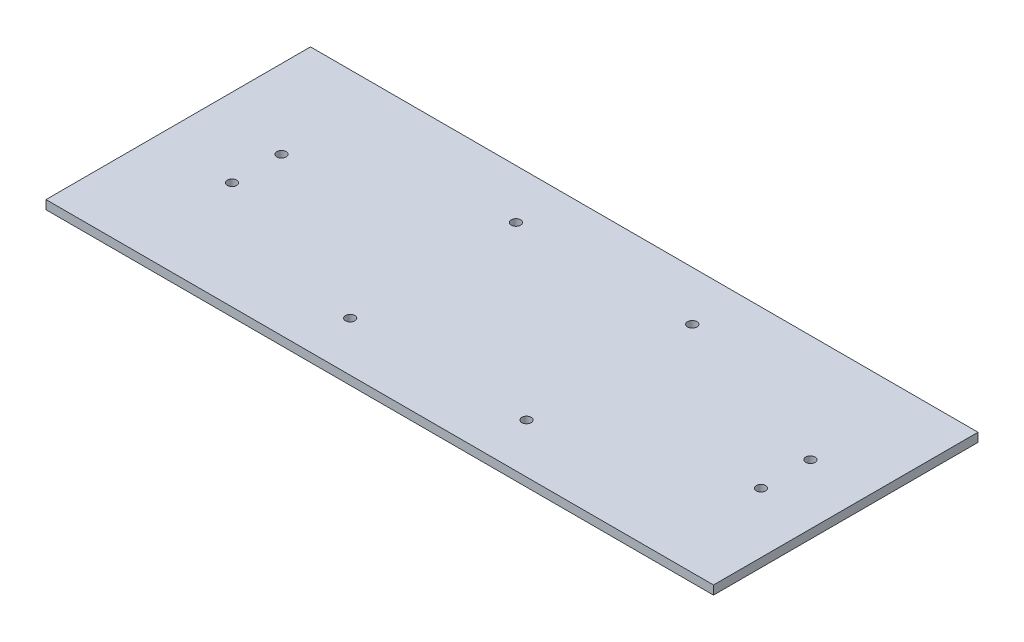
SolidWorks part; units mm, degrees
ref_plane "Front Plane" through (0, 0, 0) normal (0, 0, 1) x (1, 0, 0)
ref_plane "Top Plane" through (0, 0, 0) normal (0, 1, 0) x (1, 0, 0)
ref_plane "Right Plane" through (0, 0, 0) normal (1, 0, 0) x (0, 0, -1)
sketch "Sketch1" plane through (0, 0, 0) normal (0, 1, 0) x (1, 0, 0)
  line L1 (0, 8.5) -> (378.54, 8.5)
  line L2 (0, 8.5) -> (0, 158.5)
  line L3 (0, 158.5) -> (378.54, 158.5)
  line L4 (378.54, 8.5) -> (378.54, 158.5)
  circle A0 centre (344.5, 69.5) radius 2.65
  circle A1 centre (144.5, 36.5) radius 2.65
  circle A2 centre (244.5, 36.5) radius 2.65
  circle A3 centre (344.5, 97.5) radius 2.65
  circle A4 centre (44.5, 69.5) radius 2.65
  circle A5 centre (244.5, 130.5) radius 2.65
  circle A6 centre (144.5, 130.5) radius 2.65
  circle A7 centre (44.5, 97.5) radius 2.65
  dimension "D12" = 100
  dimension "D9" = 100
  dimension "D13" = 100
  dimension "D17" = 5.3
  dimension "D11" = 5.3
  dimension "D2" = 378.54
  dimension "D3" = 150
extrude "Boss-Extrude1" add sketch "Sketch1" along normal blind 5
